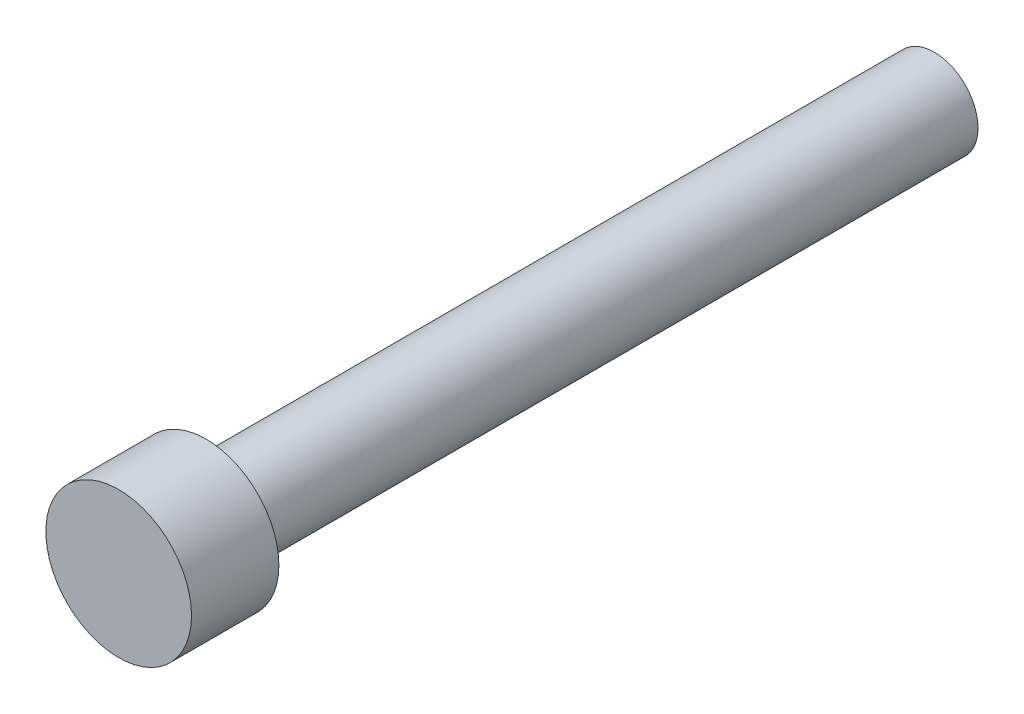
SolidWorks part; units mm, degrees
ref_plane "前视基准面" through (0, 0, 0) normal (0, 0, 1) x (1, 0, 0)
ref_plane "上视基准面" through (0, 0, 0) normal (0, 1, 0) x (1, 0, 0)
ref_plane "右视基准面" through (0, 0, 0) normal (1, 0, 0) x (0, 0, -1)
other "Configuration Table"
sketch "草图1" plane through (0, 0, 0) normal (0, 0, 1) x (1, 0, 0)
  circle A0 centre (0, 0) radius 3
extrude "Shank_simplified" add sketch "草图1" along normal blind 50
sketch "草图2" plane through (0, 0, 50) normal (0, 0, 1) x (1, 0, 0)
  circle A0 centre (0, 0) radius 5
extrude "Purchased_head_simplified" add sketch "草图2" along normal blind 6
